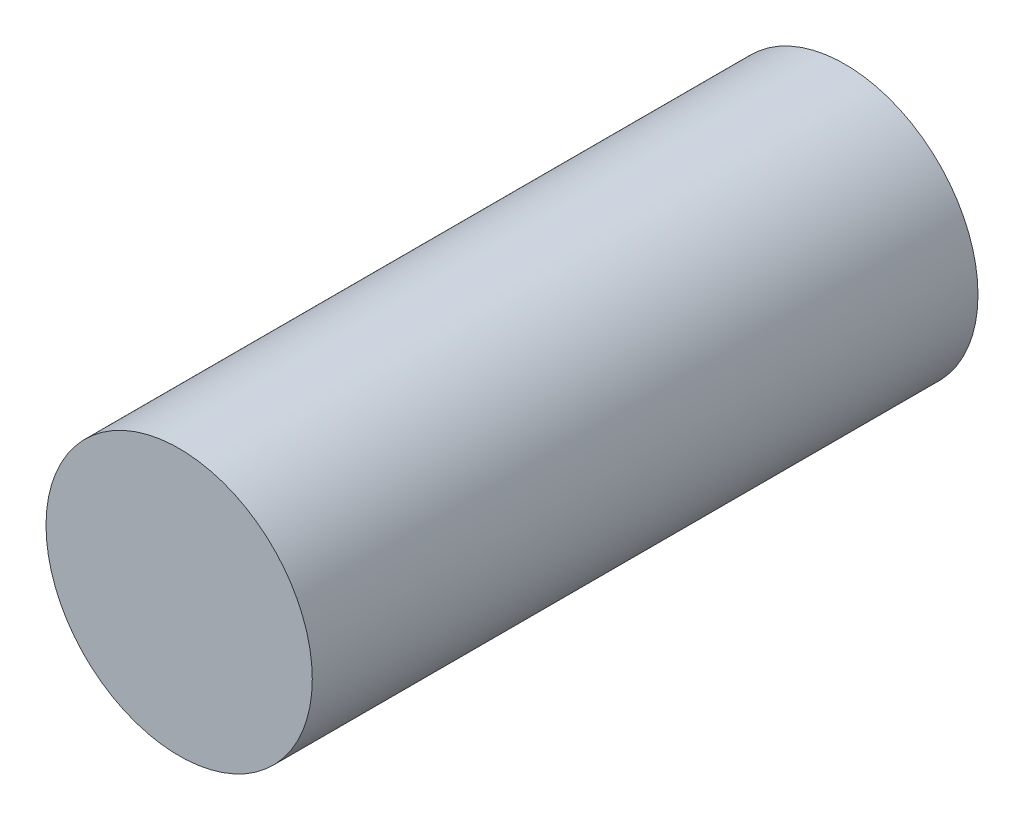
SolidWorks part; units mm, degrees
ref_plane "正面" through (0, 0, 0) normal (0, 0, 1) x (1, 0, 0)
ref_plane "平面" through (0, 0, 0) normal (0, 1, 0) x (1, 0, 0)
ref_plane "右側面" through (0, 0, 0) normal (1, 0, 0) x (0, 0, -1)
sketch "ｽｹｯﾁ1" plane through (0, 0, 0) normal (0, 0, 1) x (1, 0, 0)
  circle A0 centre (0, 0) radius 20
extrude "ﾎﾞｽ - 押し出し1" add sketch "ｽｹｯﾁ1" along normal blind 100
